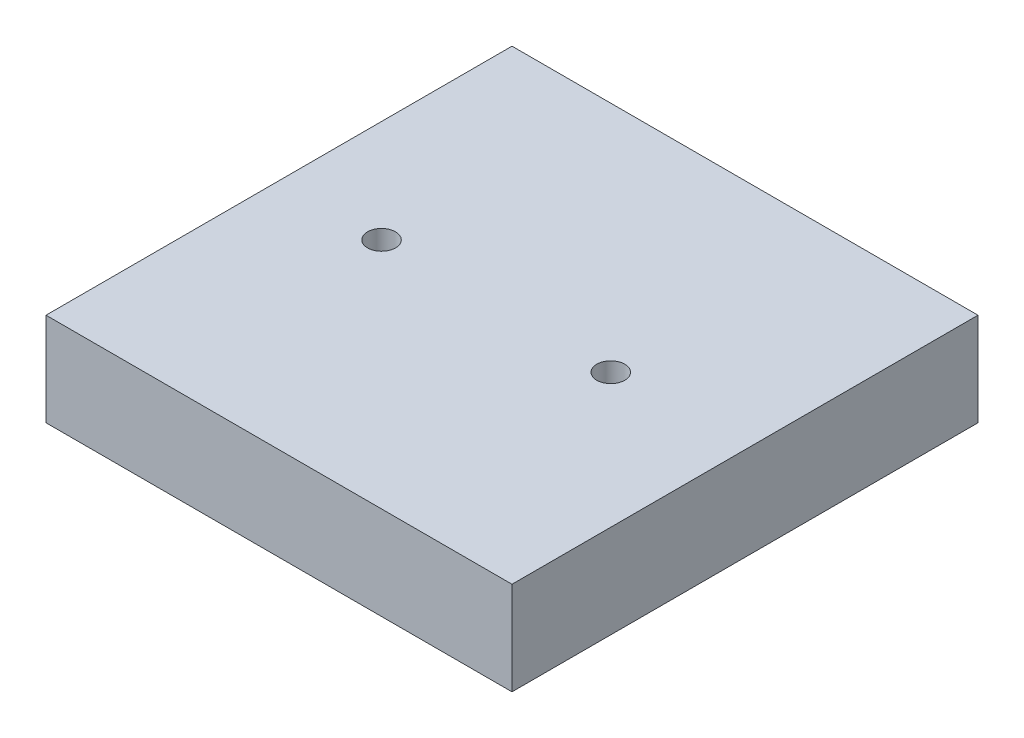
SolidWorks part; units mm, degrees
ref_plane "正面" through (0, 0, 0) normal (0, 0, 1) x (1, 0, 0)
ref_plane "平面" through (0, 0, 0) normal (0, 1, 0) x (1, 0, 0)
ref_plane "右側面" through (0, 0, 0) normal (1, 0, 0) x (0, 0, -1)
sketch "ｽｹｯﾁ1" plane through (0, 0, 0) normal (0, 1, 0) x (1, 0, 0)
  line L0 (0, 0) -> (25, 0)
  line L1 (-25, -25) -> (25, -25)
  line L2 (-25, -25) -> (-25, 25)
  line L3 (-25, 25) -> (25, 25)
  line L4 (25, -25) -> (25, 25)
  line L5 (-25, -25) -> (25, 25) construction
  line L6 (-25, 25) -> (25, -25) construction
  line L7 (25, 0) -> (-25, 0)
  circle A0 centre (10.6, 0) radius 1.5
  circle A1 centre (-14, 0) radius 1.5
  point P0 (0, 0)
  dimension "D3" = 3
  dimension "D4" = 3
  dimension "D5" = 24.6
  dimension "D1" = 50
  dimension "D2" = 50
  dimension "D6" = 14
extrude "ﾎﾞｽ - 押し出し1" add sketch "ｽｹｯﾁ1" along normal blind 10 contours A1 L7 L0 A0 L4 L3 L2 | A1 L7 L2 L1 L4 L0 A0
